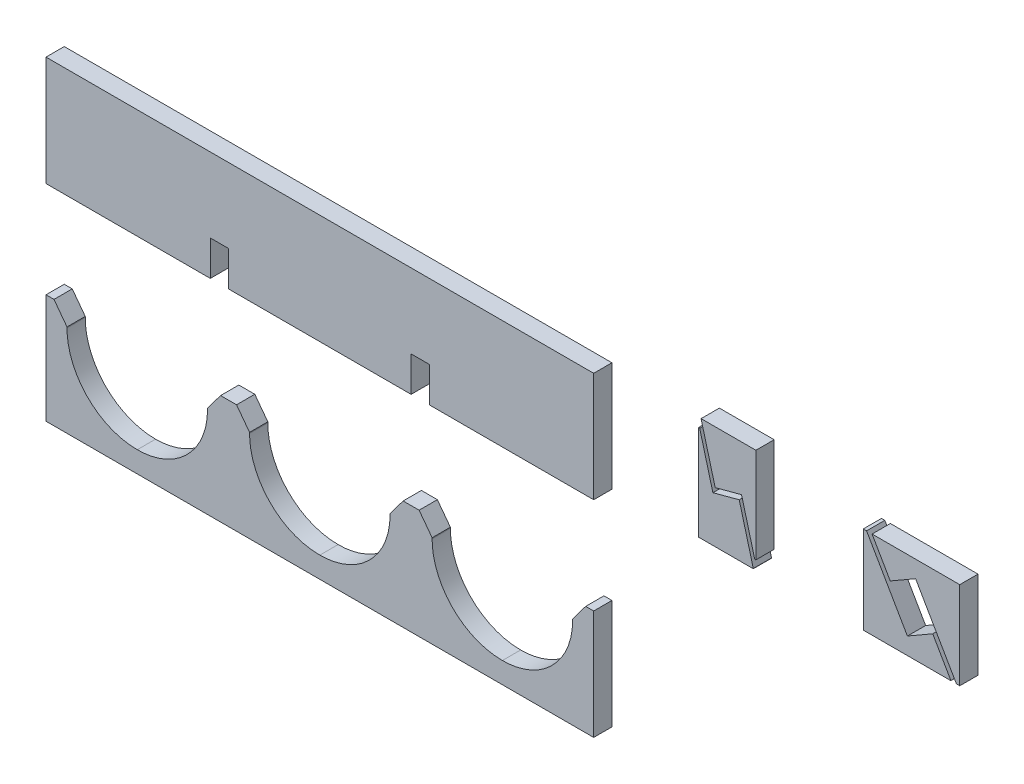
SolidWorks part; units mm, degrees
ref_plane "Plan de face" through (0, 0, 0) normal (0, 0, 1) x (1, 0, 0)
ref_plane "Plan de dessus" through (0, 0, 0) normal (0, 1, 0) x (1, 0, 0)
ref_plane "Plan de droite" through (0, 0, 0) normal (1, 0, 0) x (0, 0, -1)
sketch "Model" plane through (0, 0, 0) normal (0, 0, 1) x (1, 0, 0)
  line L0 (245.9874, -237.2413) -> (238.8578, -227.7328)
  line L1 (238.8578, -227.7328) -> (230.1045, -227.7328)
  line L2 (230.1045, -227.7328) -> (222.975, -237.2414)
  line L3 (145.9874, -237.2413) -> (138.8578, -227.7328)
  line L4 (138.8578, -227.7328) -> (130.1045, -227.7328)
  line L5 (130.1045, -227.7328) -> (122.975, -237.2414)
  line L6 (45.9874, -237.2413) -> (38.8578, -227.7328)
  line L7 (38.8578, -227.7328) -> (34.4812, -227.7328)
  line L8 (34.4812, -227.7328) -> (34.4812, -287.7328)
  line L9 (34.4812, -287.7328) -> (334.4812, -287.7328)
  line L10 (334.4812, -287.7328) -> (334.4812, -227.7328)
  line L11 (334.4812, -227.7328) -> (330.1046, -227.7328)
  line L12 (330.1046, -227.7328) -> (322.9749, -237.2414)
  line L13 (414.2075, -135.117) -> (399.7789, -138.9831)
  line L14 (399.7789, -138.9831) -> (392.5466, -111.992)
  line L15 (392.5466, -111.992) -> (391.9136, -111.992)
  line L16 (391.9136, -111.992) -> (391.9136, -163.992)
  line L17 (391.9136, -163.992) -> (421.9136, -163.992)
  line L18 (421.9136, -163.992) -> (421.9136, -163.8765)
  line L19 (421.9136, -163.8765) -> (414.2075, -135.117)
  line L20 (401.0381, -135.9304) -> (415.4667, -132.0642)
  line L21 (415.4667, -132.0642) -> (422.6989, -159.0553)
  line L22 (422.6989, -159.0553) -> (423.332, -159.0553)
  line L23 (423.332, -159.0553) -> (423.332, -107.0553)
  line L24 (423.332, -107.0553) -> (393.332, -107.0553)
  line L25 (393.332, -107.0553) -> (393.332, -107.1709)
  line L26 (393.332, -107.1709) -> (401.0381, -135.9304)
  line L27 (34.4812, -114.9778) -> (34.4812, -174.9778)
  line L28 (34.4812, -174.9778) -> (124.4812, -174.9778)
  line L29 (124.4812, -174.9778) -> (124.4812, -164.9778)
  line L30 (124.4812, -164.9778) -> (124.4812, -155.7764)
  line L31 (124.4812, -155.7764) -> (134.4812, -155.7764)
  line L32 (134.4812, -155.7764) -> (134.4812, -164.9778)
  line L33 (134.4812, -164.9778) -> (134.4812, -174.9778)
  line L34 (134.4812, -174.9778) -> (234.4812, -174.9778)
  line L35 (234.4812, -174.9778) -> (234.4812, -164.9778)
  line L36 (234.4812, -164.9778) -> (234.4812, -155.7764)
  line L37 (234.4812, -155.7764) -> (244.4812, -155.7764)
  line L38 (244.4812, -155.7764) -> (244.4812, -164.9778)
  line L39 (244.4812, -164.9778) -> (244.4812, -174.9778)
  line L40 (244.4812, -174.9778) -> (334.4812, -174.9778)
  line L41 (334.4812, -174.9778) -> (334.4812, -114.9778)
  line L42 (334.4812, -114.9778) -> (34.4812, -114.9778)
  line L43 (520.1995, -145.694) -> (506.322, -153.7062)
  line L44 (506.322, -153.7062) -> (483.9621, -114.9778)
  line L45 (483.9621, -114.9778) -> (482.1429, -114.9778)
  line L46 (482.1429, -114.9778) -> (482.1429, -162.9778)
  line L47 (482.1429, -162.9778) -> (530.1429, -162.9778)
  line L48 (530.1429, -162.9778) -> (530.1429, -162.9163)
  line L49 (530.1429, -162.9163) -> (520.1995, -145.694)
  line L50 (496.9421, -132.2616) -> (510.8197, -124.2494)
  line L51 (510.8197, -124.2494) -> (533.1795, -162.9778)
  line L52 (533.1795, -162.9778) -> (534.9988, -162.9778)
  line L53 (534.9988, -162.9778) -> (534.9988, -114.9778)
  line L54 (534.9988, -114.9778) -> (486.9988, -114.9778)
  line L55 (486.9988, -114.9778) -> (486.9988, -115.0393)
  line L56 (486.9988, -115.0393) -> (496.9421, -132.2616)
  spline S0 degree 3 poles (322.9749, -237.2414) (322.977, -237.4052) (322.9812, -237.5685) (322.9812, -237.7328) knots 0 0 0 0 1 1 1 1
  spline S1 degree 3 poles (322.9812, -237.7328) (322.9812, -258.9958) (305.7441, -276.2328) (284.4812, -276.2328) knots 1 1 1 1 2 2 2 2
  spline S2 degree 3 poles (284.4812, -276.2328) (263.2182, -276.2328) (245.9812, -258.9958) (245.9812, -237.7328) knots 2 2 2 2 3 3 3 3
  spline S3 degree 3 poles (245.9812, -237.7328) (245.9812, -237.5685) (245.9854, -237.4052) (245.9874, -237.2413) knots 3 3 3 3 4 4 4 4
  spline S4 degree 3 poles (222.975, -237.2414) (222.977, -237.4052) (222.9812, -237.5685) (222.9812, -237.7328) knots 7 7 7 7 8 8 8 8
  spline S5 degree 3 poles (222.9812, -237.7328) (222.9812, -258.9958) (205.7441, -276.2328) (184.4812, -276.2328) knots 8 8 8 8 9 9 9 9
  spline S6 degree 3 poles (184.4812, -276.2328) (163.2182, -276.2328) (145.9812, -258.9958) (145.9812, -237.7328) knots 9 9 9 9 10 10 10 10
  spline S7 degree 3 poles (145.9812, -237.7328) (145.9812, -237.5685) (145.9854, -237.4052) (145.9874, -237.2413) knots 10 10 10 10 11 11 11 11
  spline S8 degree 3 poles (122.975, -237.2414) (122.977, -237.4052) (122.9812, -237.5685) (122.9812, -237.7328) knots 14 14 14 14 15 15 15 15
  spline S9 degree 3 poles (122.9812, -237.7328) (122.9812, -258.9958) (105.7441, -276.2328) (84.4812, -276.2328) knots 15 15 15 15 16 16 16 16
  spline S10 degree 3 poles (84.4812, -276.2328) (63.2182, -276.2328) (45.9812, -258.9958) (45.9812, -237.7328) knots 16 16 16 16 17 17 17 17
  spline S11 degree 3 poles (45.9812, -237.7328) (45.9812, -237.5685) (45.9853, -237.4052) (45.9874, -237.2413) knots 17 17 17 17 18 18 18 18
extrude "Boss.-Extru.1" add sketch "Model" along normal blind 10
